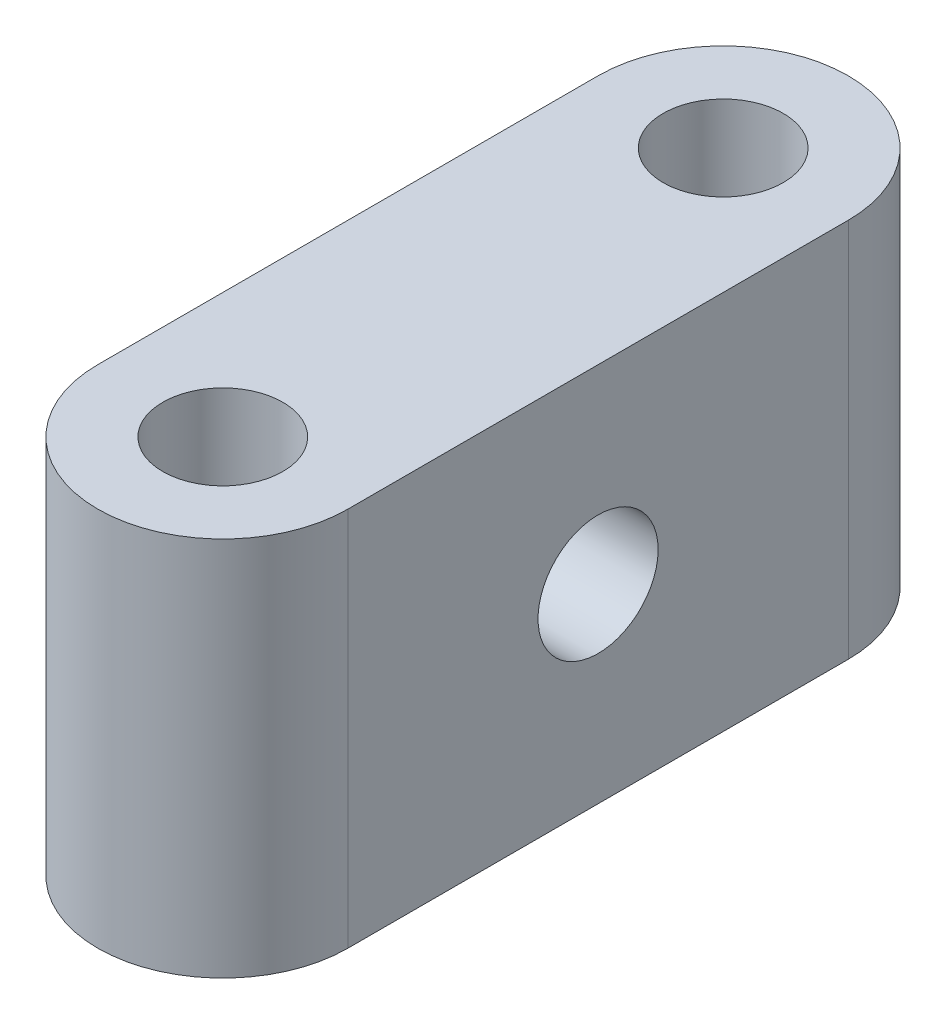
SolidWorks part; units mm, degrees
ref_plane "Front Plane" through (0, 0, 0) normal (0, 0, 1) x (1, 0, 0)
ref_plane "Top Plane" through (0, 0, 0) normal (0, 1, 0) x (1, 0, 0)
ref_plane "Right Plane" through (0, 0, 0) normal (1, 0, 0) x (0, 0, -1)
sketch "Sketch2" plane through (0, 0, 0) normal (0, 1, 0) x (1, 0, 0)
  line L0 (0, -25) -> (0, 25) construction
  line L1 (-12.5, -25) -> (-12.5, 25)
  line L2 (12.5, -25) -> (12.5, 25)
  arc A0 (-12.5, -25) -> (12.5, -25) centre (0, -25) ccw
  arc A1 (12.5, 25) -> (-12.5, 25) centre (0, 25) ccw
  circle A2 centre (0, 25) radius 6
  circle A3 centre (0, -25) radius 6
  point P2 (0, 0)
  dimension "D1" = 12.5
  dimension "D2" = 12
  dimension "D3" = 50
extrude "Boss-Extrude1" add sketch "Sketch2" along normal mid plane 38
sketch "Sketch5" plane through (12.5, 0, 0) normal (1, 0, 0) x (0, 0, -1)
  circle A0 centre (0, 0) radius 6
  dimension "D1" = 12
extrude "Cut-Extrude1" cut sketch "Sketch5" against normal blind 12.5
